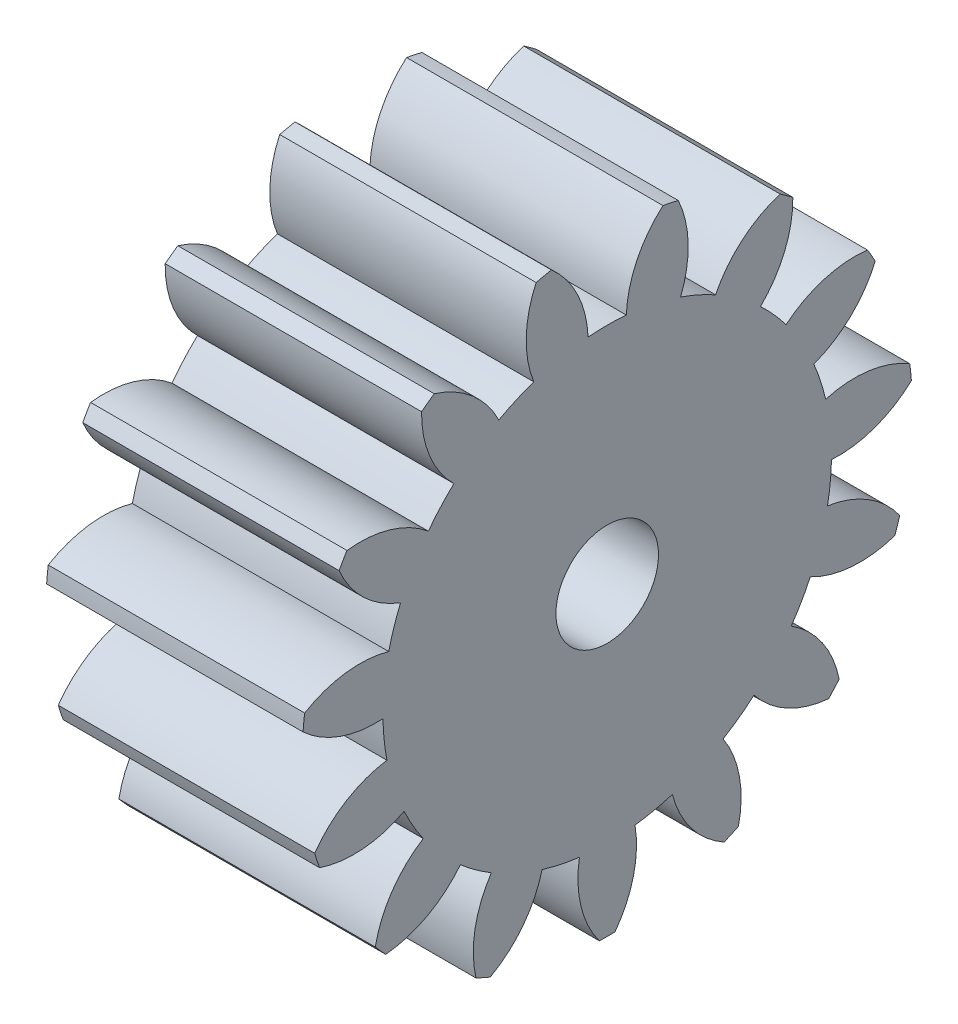
SolidWorks part; units mm, degrees
ref_plane "Plane1" through (0, 0, 0) normal (0, 0, 1) x (1, 0, 0)
ref_plane "Plane2" through (0, 0, 0) normal (0, 1, 0) x (1, 0, 0)
ref_plane "Plane3" through (0, 0, 0) normal (1, 0, 0) x (0, 0, -1)
sketch "HoldingSke" plane through (0, 0, 0) normal (0, 1, 0) x (1, 0, 0)
  line L0 (0, 0) -> (1.3799, -0.3697)
  line L1 (-15, 0) -> (100, 0) construction
  line L2 (0, 0) -> (-2.1039, 2.3779)
  line L3 (0, 0) -> (-11.863, 4.5341)
  line L4 (0, 0) -> (8.3417, 2.2352)
  line L5 (0, 0) -> (-46.8476, -17.4728)
  line L6 (0, 0) -> (-4.1448, -2.7965)
  line L7 (-2.1039, 2.3779) -> (8.6586, 51.2059)
  line L8 (-76.2, 54.61) -> (-75.9, 54.61)
  line L9 (-71.009, 38.7566) -> (-53.1078, 45.2721)
  line L10 (-76.2, 71.12) -> (104.1128, 71.12)
  line L11 (0, 0) -> (-5, 0)
  line L12 (-76.2, 101.6) -> (-76.173, 101.6)
  line L13 (24.9733, 27.94) -> (52.9518, 28.4284)
  line L14 (24.9733, 27.94) -> (24.9743, 27.94)
  line L15 (24.9733, 27.94) -> (100.4006, 29.5858)
  line L16 (-63.627, -0.7) -> (-12.827, -0.7)
  circle A0 centre (0, 0) radius 1
  circle A1 centre (0, 0) radius 4.374
  circle A2 centre (0, 0) radius 37.5
  circle A3 centre (0, 0) radius 1
  dimension "MHD" = 8.748
  dimension "Hub_dia" = 75
  dimension "Bore" = 2
  dimension "MBD" = 2
  dimension "Num_teeth" = 15
  dimension "Pitch_radius" = 180.3128
  dimension "Pitch" = 1.4286
  dimension "Width" = 5
  dimension "Overall_len" = 50
  dimension "Show_teeth" = 15
  dimension "Thickness" = 5
  dimension "OAL" = 50.0001
  dimension "T_dim" = 0.3
  dimension "Ap" = 20
  dimension "H" = 19.05
  dimension "Backlash" = 0.027
  dimension "Addendum_fac" = 1
  dimension "Dedendum_fac" = 1.25
  dimension "Clearance_fac" = 0.25
  dimension "Dedendum_add" = 0.001
  dimension "Module" = 0.7
sketch "BasProSke" plane through (0, 0, 0) normal (0, 1, 0) x (1, 0, 0)
  line L0 (-10, 0) -> (60, 0) construction
  line L1 (0, 0) -> (0, 5.95)
  line L2 (0, 0) -> (5, 0)
  line L3 (5, 0) -> (5, 5.95)
  line L4 (5, 5.95) -> (0, 5.95)
  dimension "Diameter" = 11.9
  dimension "Thickness" = 5
revolve "Base-Revolve" add sketch "BasProSke" angle 360 about L0
sketch "TooCutSke" plane through (0, 0, 0) normal (1, 0, 0) x (0, 0, -1)
  line L1 (0, 0) -> (0, 107) construction
  line L2 (0, 0) -> (-0.596, 5.2161) construction
  line L3 (0, 0) -> (-2.1731, 10.2236) construction
  line L4 (-0.596, 5.2161) -> (-1.0865, 5.1118) construction
  arc A0 (0.3727, 4.3581) -> (-0.3727, 4.3581) centre (0, 0) ccw
  arc A1 (1.1119, 5.871) -> (-1.1119, 5.871) centre (0, 0) ccw
  circle A2 centre (0, 0) radius 5.25 construction
  circle A3 centre (0, 0) radius 4.9334 construction
  arc A4 (-0.3727, 4.3581) -> (-1.1119, 5.871) centre (-2.4708, 4.27) ccw
  arc A5 (1.1119, 5.871) -> (0.3727, 4.3581) centre (2.4708, 4.27) ccw
  dimension "Root_dia" = 8.748
  dimension "Overcut_dia" = 11.9508
  dimension "Pitch_dia" = 10.5
  dimension "Base_dia" = 9.8668
  dimension "Flank_rad" = 2.1
  dimension "Half_ang" = 12
  dimension "Half_CT" = 0.5015
extrude "ToothCut" cut sketch "TooCutSke" along normal through all
fillet "Breaks" [suppressed] radius 0.014
fillet "RootFillets" [suppressed] radius 0.176
pattern_circular "TeethCuts" count 15 every 24 about axis through (-10, 0, 0) along (1, 0, 0) of "ToothCut", "RootFillets", "Breaks"
sketch "HubNeaOneSke" plane through (0, 0, 0) normal (-1, 0, 0) x (0, 0, 1)
  circle A0 centre (0, 0) radius 4.374
  dimension "Diameter" = 8.748
extrude "HubNearOne" [suppressed] add sketch "HubNeaOneSke" along normal blind 45.0001
sketch "HubNeaBotSke" plane through (0, 0, 0) normal (-1, 0, 0) x (0, 0, 1)
  circle A0 centre (0, 0) radius 4.374
  dimension "Diameter" = 8.748
extrude "HubNearBoth" [suppressed] add sketch "HubNeaBotSke" along normal blind 22.5
ref_plane "FarPln" through (5, 0, 0) normal (1, 0, 0) x (0, 0, -1)
sketch "HubFarSke" plane through (5, 0, 0) normal (1, 0, 0) x (0, 0, -1)
  circle A0 centre (0, 0) radius 4.374
  dimension "Diameter" = 8.748
extrude "HubFar" [suppressed] add sketch "HubFarSke" along normal blind 22.5
sketch "BorSke" plane through (0, 0, 0) normal (1, 0, 0) x (0, 0, -1)
  circle A0 centre (0, 0) radius 1
  dimension "Diameter" = 2
extrude "Bore" cut sketch "BorSke" along normal mid plane 100.0001
sketch "KeySke" plane through (0, 0, 0) normal (1, 0, 0) x (0, 0, -1)
  line L0 (-0.4, 0) -> (-0.4, 1.3)
  line L1 (-0.4, 1.3) -> (0.4, 1.3)
  line L2 (0.4, 1.3) -> (0.4, 0)
  line L3 (0, 0) -> (0, 34) construction
  line L4 (-0.4, 0) -> (0.4, 0)
  dimension "Offset" = 1.3
  dimension "Width" = 0.8
extrude "Keyway" [suppressed] cut sketch "KeySke" along normal mid plane 100.0001
pattern_circular "Keyway2" [suppressed] count 2 every 90 about axis through (-10, 0, 0) along (1, 0, 0)
equation "' \"Module@HoldingSke\" = 6.35"
equation "' \"Num_teeth@HoldingSke\" = 12"
equation "' \"Ap@HoldingSke\" =  20"
equation "' \"Width@HoldingSke\" = 0.5 * 25.4"
equation "' \"Hub_dia@HoldingSke\"= 1 * 25.4"
equation "' \"Overall_len@HoldingSke\" = 1.0 * 25.4"
equation "' \"Bore@HoldingSke\" = 0.75 * 25.4"
equation "' \"T_dim@HoldingSke\" = 0.1 * 25.4"
equation "' \"Width@KeySke\" = 0.25 * 25.4"
equation "' \"Show_teeth@HoldingSke\" = 13"
equation "' \"Backlash@HoldingSke\" = 0.009 * 25.4"
equation "' \"Addendum_fac@HoldingSke\" = 1.0"
equation "' \"Dedendum_fac@HoldingSke\" = 1.25"
equation "' \"Dedendum_add@HoldingSke\" = 0.00005 * 25.4"
equation "' \"Clearance_fac@HoldingSke\" = 0.25"
equation "\"Pitch@HoldingSke\" = 1 / \"Module@HoldingSke\""
equation "\"Overcut_dia@TooCutSke\" = (\"Num_teeth@HoldingSke\" + 2 * \"Addendum_fac@HoldingSke\") / \"Pitch@HoldingSke\" + 0.002 * 25.4"
equation "\"Pitch_dia@TooCutSke\" = \"Num_teeth@HoldingSke\" / \"Pitch@HoldingSke\""
equation "\"Base_dia@TooCutSke\" = \"Num_teeth@HoldingSke\" / \"Pitch@HoldingSke\" * cos((\"Ap@HoldingSke\"  * 3.14159265 / 180))"
equation "\"Root_dia@TooCutSke\" = (\"Num_teeth@HoldingSke\" + 2) / \"Pitch@HoldingSke\" - 2 * (\"Addendum_fac@HoldingSke\" + \"Dedendum_fac@HoldingSke\") / \"Pitch@HoldingSke\" - \"Dedendum_add@HoldingSke\" * 2"
equation "\"Half_ang@TooCutSke\" = 180 / \"Num_teeth@HoldingSke\""
equation "\"Half_CT@TooCutSke\" = \"Num_teeth@HoldingSke\" / \"Pitch@HoldingSke\" * sin((3.14159265 / 2 / \"Num_teeth@HoldingSke\")) / 2 - 7 * \"Backlash@HoldingSke\" / 4"
equation "\"Flank_rad@TooCutSke\" = \"Num_teeth@HoldingSke\" / \"Pitch@HoldingSke\" / 5"
equation "\"Radius@RootFillets\" = \"Clearance_fac@HoldingSke\" / \"Pitch@HoldingSke\" + \"Dedendum_add@HoldingSke\""
equation "\"Break_rad@Breaks\" = 0.02 / \"Pitch@HoldingSke\""
equation "\"Thickness@HoldingSke\" = \"Width@HoldingSke\""
equation "\"OAL@HoldingSke\" = \"Thickness@HoldingSke\""
equation "\"MHD@HoldingSke\" = (\"Num_teeth@HoldingSke\" + 2) / \"Pitch@HoldingSke\" - 2 * (\"Addendum_fac@HoldingSke\" + \"Dedendum_fac@HoldingSke\")  / \"Pitch@HoldingSke\" - \"Dedendum_add@HoldingSke\" * 2"
equation "\"MBD@HoldingSke\" = (\"Num_teeth@HoldingSke\" + 2) / \"Pitch@HoldingSke\" - 2 * (\"Addendum_fac@HoldingSke\" + \"Dedendum_fac@HoldingSke\")  / \"Pitch@HoldingSke\" - \"Dedendum_add@HoldingSke\" * 2 - 0.002 * 25.4"
equation "\"MHD@HoldingSke\" = ((sgn( \"MHD@HoldingSke\" - \"Hub_dia@HoldingSke\" )-1)*( \"MHD@HoldingSke\" - \"Hub_dia@HoldingSke\" ))/-2+ \"Hub_dia@HoldingSke\""
equation "\"MBD@HoldingSke\" = ((sgn( \"MBD@HoldingSke\" - \"Bore@HoldingSke\" )-1)*( \"MBD@HoldingSke\" - \"Bore@HoldingSke\" ))/-2+ \"Bore@HoldingSke\""
equation "\"OAL@HoldingSke\" = ((sgn( \"OAL@HoldingSke\" - \"Overall_len@HoldingSke\" )+1)*( \"OAL@HoldingSke\" - \"Overall_len@HoldingSke\" ))/2 + \"Overall_len@HoldingSke\" + 0.000002 * 25.4"
equation "\"Num_teeth@TeethCuts\" = int( \"Show_teeth@HoldingSke\" ) + 1"
equation "\"Num_teeth@TeethCuts\" = ((sgn( \"Num_teeth@TeethCuts\" - \"Num_teeth@HoldingSke\" )-1)*( \"Num_teeth@TeethCuts\" - \"Num_teeth@HoldingSke\" ))/-2+ \"Num_teeth@HoldingSke\""
equation "\"Num_teeth@TeethCuts\" = ((sgn( \"Num_teeth@TeethCuts\" - 2.0)+1)*( \"Num_teeth@TeethCuts\" - 2.0))/2 +2.0"
equation "\"Angle@TeethCuts\" = 360.0 / \"Num_teeth@HoldingSke\""
equation "\"Diameter@BasProSke\" = (\"Num_teeth@HoldingSke\" + 2 * \"Addendum_fac@HoldingSke\") / \"Pitch@HoldingSke\""
equation "\"Thickness@BasProSke\"  = \"Thickness@HoldingSke\""
equation "' \"Fillet_rad@BasProSke\" =  \"Thickness@HoldingSke\" * 0.05"
equation "\"MHD@HoldingSke\" = ((sgn( \"MHD@HoldingSke\" - \"Root_dia@TooCutSke\" )-1)*( \"MHD@HoldingSke\" - \"Root_dia@TooCutSke\" ))/-2+ \"Root_dia@TooCutSke\""
equation "\"Diameter@HubNeaOneSke\" = \"MHD@HoldingSke\""
equation "\"Length@HubNearOne\" = \"OAL@HoldingSke\" - \"Thickness@BasProSke\""
equation "\"Diameter@HubNeaBotSke\" = \"MHD@HoldingSke\""
equation "\"Length@HubNearBoth\" = ( \"OAL@HoldingSke\" - \"Thickness@BasProSke\" ) / 2.0"
equation "\"Thickness@FarPln\" = \"Thickness@BasProSke\""
equation "\"Diameter@HubFarSke\" = \"MHD@HoldingSke\""
equation "\"Length@HubFar\" = ( \"OAL@HoldingSke\" - \"Thickness@BasProSke\" ) / 2.0"
equation "\"Diameter@BorSke\" = \"MBD@HoldingSke\""
equation "\"D1@Bore\" = \"OAL@HoldingSke\" * 2.0"
equation "\"D1@Keyway\" = \"OAL@HoldingSke\" * 2.0"
equation "\"Offset@KeySke\" = \"T_dim@HoldingSke\" + \"MBD@HoldingSke\" / 2.0"
